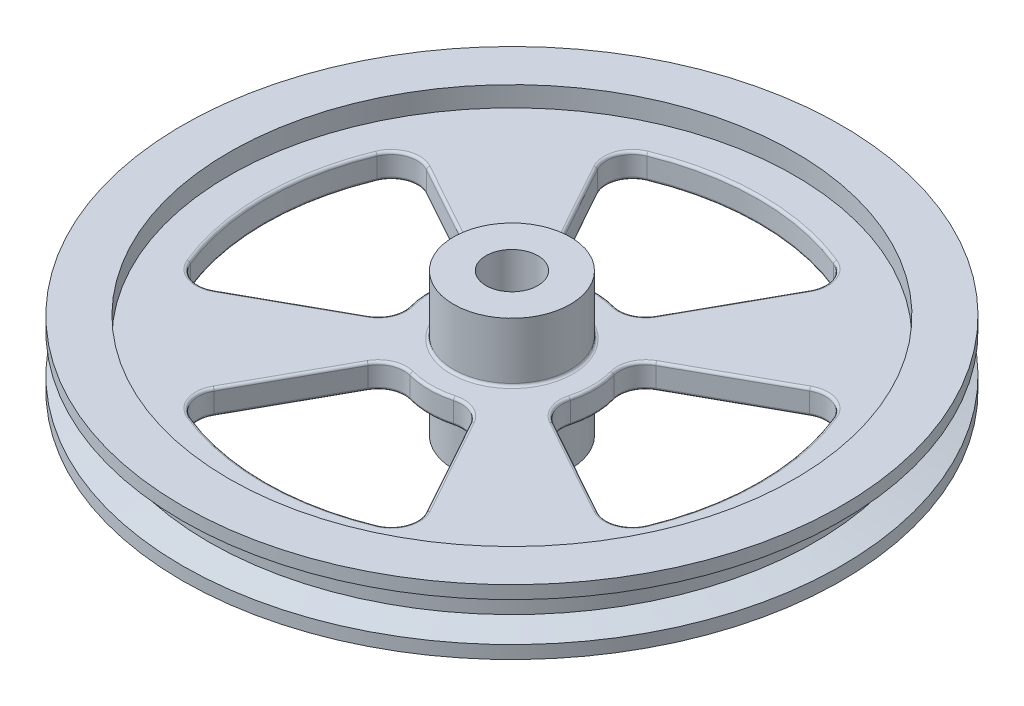
SolidWorks part; units mm, degrees
ref_plane "Front Plane" through (0, 0, 0) normal (0, 0, 1) x (1, 0, 0)
ref_plane "Top Plane" through (0, 0, 0) normal (0, 1, 0) x (1, 0, 0)
ref_plane "Right Plane" through (0, 0, 0) normal (1, 0, 0) x (0, 0, -1)
sketch "Sketch3" plane through (0, 0, 0) normal (0, 0, 1) x (1, 0, 0)
  line L0 (0, 118.75) -> (0, -113.1944) construction
  line L1 (-293.75, 0) -> (308.1019, 0) construction
  line L2 (-10, 27.5) -> (-10, -27.5)
  line L3 (-10, -27.5) -> (-22.5, -27.5)
  line L4 (-22.5, -27.5) -> (-22.5, -12.5)
  line L5 (-109, -12.5) -> (-127, -12.5)
  line L6 (-127, -12.5) -> (-127, -7.5)
  line L7 (-127, -7.5) -> (-116.7369, -4.75)
  line L8 (-116.7369, -4.75) -> (-116.7369, 4.75)
  line L9 (-116.7369, 4.75) -> (-127, 7.5)
  line L10 (-127, 7.5) -> (-127, 12.5)
  line L11 (-127, 12.5) -> (-109, 12.5)
  line L12 (-22.5, 12.5) -> (-22.5, 27.5)
  line L13 (-22.5, 27.5) -> (-10, 27.5)
  line L14 (-109, 12.5) -> (-109, 4.75)
  line L15 (-22.5, 12.5) -> (-22.5, 4.75)
  line L16 (-109, 4.75) -> (-22.5, 4.75)
  line L17 (-109, -4.75) -> (-22.5, -4.75)
  line L18 (-22.5, -4.75) -> (-22.5, -12.5)
  line L19 (-109, -4.75) -> (-109, -12.5)
  dimension "D1" = 22.5
  dimension "D2" = 10
  dimension "D3" = 127
  dimension "D4" = 9.5
  dimension "D5" = 30
  dimension "D6" = 15
  dimension "D7" = 25
  dimension "D8" = 55
  dimension "D9" = 109
revolve "Revolve1" add sketch "Sketch3" angle 360 about L0
sketch "Sketch4" plane through (0, 4.75, 0) normal (0, 1, 0) x (1, 0, 0)
  line L0 (0, 44.3119) -> (0, -95) construction
  line L1 (-19.7764, 35.6776) -> (-40.9226, 73.8264)
  line L2 (19.7764, 35.6776) -> (40.9226, 73.8264)
  line L3 (35.6776, 19.7764) -> (73.8264, 40.9226)
  line L4 (35.6776, -19.7764) -> (73.8264, -40.9226)
  line L5 (19.7764, -35.6776) -> (40.9226, -73.8264)
  line L6 (-19.7764, -35.6776) -> (-40.9226, -73.8264)
  line L7 (-35.6776, -19.7764) -> (-73.8264, -40.9226)
  line L8 (-35.6776, 19.7764) -> (-73.8264, 40.9226)
  arc A0 (35.9619, 87.9303) -> (-35.9619, 87.9303) centre (0, 0) ccw
  arc A1 (8.404, 30.8767) -> (-8.404, 30.8767) centre (0, 0) ccw
  arc A2 (-35.9619, 87.9303) -> (-40.9226, 73.8264) centre (-32.1764, 78.6745) ccw
  arc A3 (40.9226, 73.8264) -> (35.9619, 87.9303) centre (32.1764, 78.6745) ccw
  arc A5 (-19.7764, 35.6776) -> (-8.404, 30.8767) centre (-11.0302, 40.5257) ccw
  arc A6 (8.404, 30.8767) -> (19.7764, 35.6776) centre (11.0302, 40.5257) ccw
  circle A7 centre (0, 0) radius 95 construction
  circle A8 centre (0, 0) radius 95 construction
  arc A9 (35.6776, 19.7764) -> (30.8767, 8.404) centre (40.5257, 11.0302) ccw
  arc A10 (30.8767, -8.404) -> (30.8767, 8.404) centre (0, 0) ccw
  arc A11 (30.8767, -8.404) -> (35.6776, -19.7764) centre (40.5257, -11.0302) ccw
  arc A12 (73.8264, -40.9226) -> (87.9303, -35.9619) centre (78.6745, -32.1764) ccw
  arc A13 (87.9303, -35.9619) -> (87.9303, 35.9619) centre (0, 0) ccw
  arc A14 (87.9303, 35.9619) -> (73.8264, 40.9226) centre (78.6745, 32.1764) ccw
  circle A15 centre (0, 0) radius 95 construction
  arc A16 (19.7764, -35.6776) -> (8.404, -30.8767) centre (11.0302, -40.5257) ccw
  arc A17 (-8.404, -30.8767) -> (8.404, -30.8767) centre (0, 0) ccw
  arc A18 (-8.404, -30.8767) -> (-19.7764, -35.6776) centre (-11.0302, -40.5257) ccw
  arc A19 (-40.9226, -73.8264) -> (-35.9619, -87.9303) centre (-32.1764, -78.6745) ccw
  arc A20 (-35.9619, -87.9303) -> (35.9619, -87.9303) centre (0, 0) ccw
  arc A21 (35.9619, -87.9303) -> (40.9226, -73.8264) centre (32.1764, -78.6745) ccw
  circle A22 centre (0, 0) radius 95 construction
  arc A23 (-35.6776, -19.7764) -> (-30.8767, -8.404) centre (-40.5257, -11.0302) ccw
  arc A24 (-30.8767, 8.404) -> (-30.8767, -8.404) centre (0, 0) ccw
  arc A25 (-30.8767, 8.404) -> (-35.6776, 19.7764) centre (-40.5257, 11.0302) ccw
  arc A26 (-73.8264, 40.9226) -> (-87.9303, 35.9619) centre (-78.6745, 32.1764) ccw
  arc A27 (-87.9303, 35.9619) -> (-87.9303, -35.9619) centre (0, 0) ccw
  arc A28 (-87.9303, -35.9619) -> (-73.8264, -40.9226) centre (-78.6745, -32.1764) ccw
  point P6 (0, 95)
  point P60 (0, 0)
  dimension "D1" = 95
  dimension "D2" = 32
  dimension "D5" = 35.9619
  dimension "D4" = 10
  dimension "D6" = 190
  dimension "D3" = 58
  dimension "D7" = 4
extrude "Cut-Extrude1" cut sketch "Sketch4" against normal blind 10
fillet "Fillet1" radius 1 1 edges at (0, 4.75, 22.5)
fillet "Fillet2" radius 1 33 edges at (0, -4.75, 22.5) (-14.9194, 4.75, -31.313) (-30.3495, 4.75, -54.752) (-41.6099, 4.75, -81.9925) (0, 4.75, -95) (41.6099, 4.75, -81.9925) (30.3495, 4.75, -54.752) (14.9194, 4.75, -31.313) (0, 4.75, -32) (-14.9194, -4.75, -31.313) (-30.3495, -4.75, -54.752) (-41.6099, -4.75, -81.9925) (0, -4.75, -95) (41.6099, -4.75, -81.9925) (30.3495, -4.75, -54.752) (14.9194, -4.75, -31.313) (0, -4.75, -32) (31.313, -4.75, -14.9194) (32, -4.75, 0) (31.313, -4.75, 14.9194) (54.752, -4.75, 30.3495) (81.9925, -4.75, 41.6099) (95, -4.75, 0) (81.9925, -4.75, -41.6099) (54.752, -4.75, -30.3495) (81.9925, 4.75, 41.6099) (31.313, 4.75, 14.9194) (54.752, 4.75, 30.3495) (32, 4.75, 0) (31.313, 4.75, -14.9194) (81.9925, 4.75, -41.6099) (54.752, 4.75, -30.3495) (95, 4.75, 0)
fillet "Fillet3" radius 1 32 edges at (-14.9194, -4.75, 31.313) (-41.6099, -4.75, 81.9925) (-30.3495, -4.75, 54.752) (0, -4.75, 95) (41.6099, -4.75, 81.9925) (30.3495, -4.75, 54.752) (14.9194, -4.75, 31.313) (0, -4.75, 32) (-14.9194, 4.75, 31.313) (0, 4.75, 32) (14.9194, 4.75, 31.313) (30.3495, 4.75, 54.752) (41.6099, 4.75, 81.9925) (0, 4.75, 95) (-41.6099, 4.75, 81.9925) (-30.3495, 4.75, 54.752) (-31.313, -4.75, 14.9194) (-54.752, -4.75, 30.3495) (-81.9925, -4.75, 41.6099) (-95, -4.75, 0) (-81.9925, -4.75, -41.6099) (-54.752, -4.75, -30.3495) (-31.313, -4.75, -14.9194) (-32, -4.75, 0) (-81.9925, 4.75, -41.6099) (-95, 4.75, 0) (-81.9925, 4.75, 41.6099) (-54.752, 4.75, 30.3495) (-31.313, 4.75, 14.9194) (-32, 4.75, 0) (-31.313, 4.75, -14.9194) (-54.752, 4.75, -30.3495)
